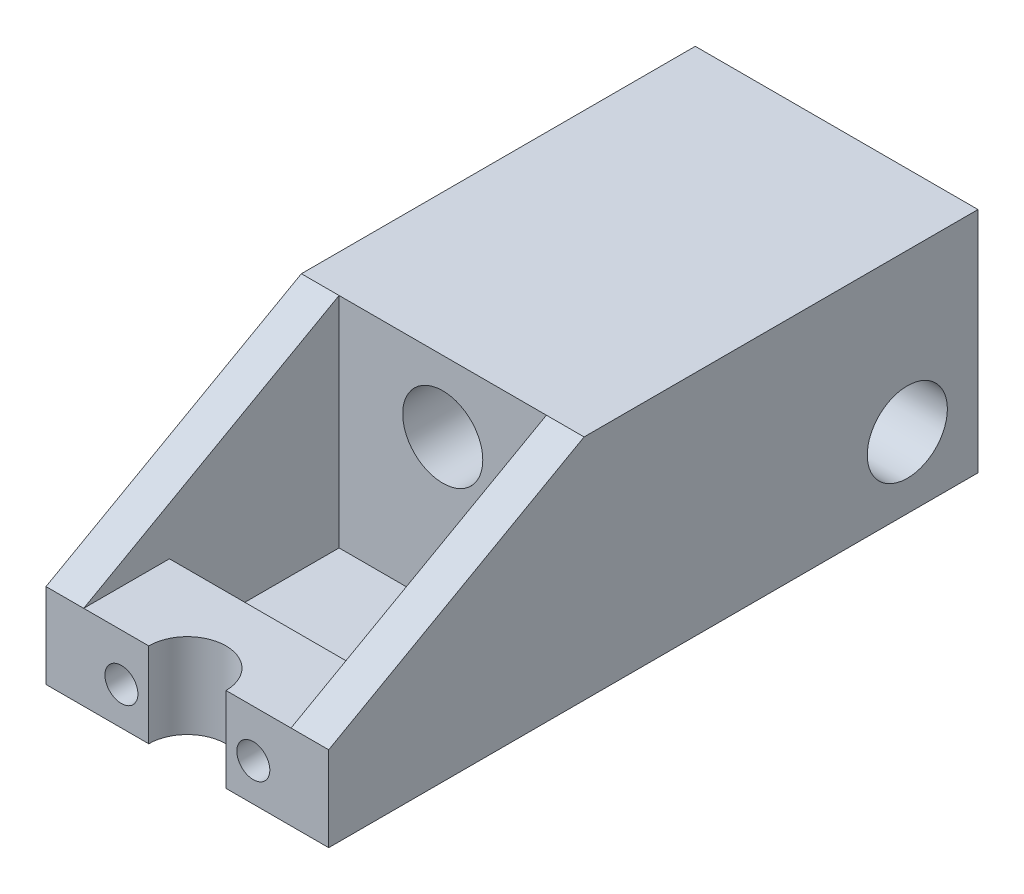
SolidWorks part; units mm, degrees
ref_plane "Piano frontale" through (0, 0, 0) normal (0, 0, 1) x (1, 0, 0)
ref_plane "Piano superiore" through (0, 0, 0) normal (0, 1, 0) x (1, 0, 0)
ref_plane "Piano destro" through (0, 0, 0) normal (1, 0, 0) x (0, 0, -1)
sketch "Schizzo7" plane through (0, 0, 0) normal (0, 0, 1) x (1, 0, 0)
  line L0 (0, -12.1) -> (0, 12.1) construction
  line L1 (15, -12.1) -> (-15, -12.1)
  line L2 (15, -12.1) -> (15, 12.1)
  line L3 (15, 12.1) -> (-15, 12.1)
  line L4 (-15, -12.1) -> (-15, 12.1)
  line L5 (15, -12.1) -> (-15, 12.1) construction
  line L6 (15, 12.1) -> (-15, -12.1) construction
  circle A0 centre (0, 4.6) radius 4.25
  point P0 (0, 0)
  point P10 (0, -4.6)
  dimension "D3" = 8.5
  dimension "D5" = 7.5
  dimension "D1" = 7.5
  dimension "D2" = 30
  dimension "D4" = 9.2
extrude "Estrusione-Estrusione3" add sketch "Schizzo7" along normal mid plane 15
sketch "Schizzo8" plane through (15, 0, 0) normal (1, 0, 0) x (0, 0, -1)
  line L0 (0, 12.1) -> (0, -12.1) construction
  line L1 (-7.5, 12.1) -> (7.5, 12.1) construction
  line L2 (-7.5, -12.1) -> (7.5, -12.1) construction
  circle A0 centre (0, -4.6) radius 4.25
  dimension "D2" = 8.5
  dimension "D1" = 7.5
extrude "Taglio-Estrusione1" cut sketch "Schizzo8" against normal up to next
sketch "Schizzo12" plane through (0, 0, 7.5) normal (0, 0, 1) x (1, 0, 0)
  line L0 (15, -12.1) -> (15, 12.1) construction
  line L1 (-15, -12.1) -> (15, -12.1)
  line L2 (-15, -12.1) -> (-15, -3.1)
  line L3 (-15, -3.1) -> (15, -3.1)
  line L4 (15, -12.1) -> (15, -3.1)
  dimension "D1" = 9
extrude "Estrusione-Estrusione5" add sketch "Schizzo12" along normal blind 53.9
sketch "Schizzo14" plane through (0, -3.1, 0) normal (0, 1, 0) x (1, 0, 0)
  line L0 (15, -61.4) -> (-15, -61.4) construction
  line L1 (4.1, -61.4) -> (-4.1, -61.4)
  arc A0 (4.1, -61.4) -> (-4.1, -61.4) centre (0, -61.4) ccw
  dimension "D1" = 4.1
extrude "Taglio-Estrusione3" cut sketch "Schizzo14" against normal up to next contours A0 L1
sketch "Schizzo15" plane through (0, -3.1, 0) normal (0, 1, 0) x (1, 0, 0)
  line L0 (15, -61.4) -> (4.1, -61.4) construction
  line L1 (0, -57.3) -> (0, -7.5) construction
  line L2 (15, -7.5) -> (-15, -7.5) construction
  line L3 (11, -52.3) -> (11, -34.3)
  line L4 (11, -34.3) -> (-11, -34.3)
  line L5 (-11, -52.3) -> (-11, -34.3)
  line L7 (15, -61.4) -> (15, -7.5) construction
  line L12 (11, -52.3) -> (-11, -52.3)
  arc A0 (4.1, -61.4) -> (-4.1, -61.4) centre (0, -61.4) ccw construction
  point P17 (0, -34.3)
  point P18 (0, -52.3)
  dimension "D1" = 9.1
  dimension "D2" = 18
  dimension "D4" = 4
sketch "Schizzo16" plane through (0, 0, 61.4) normal (0, 0, 1) x (1, 0, 0)
  line L0 (-4.1, -12.1) -> (4.1, -12.1) construction
  line L1 (-4.1, -12.1) -> (4.1, -12.1) construction
  line L2 (4.1, -3.1) -> (-4.1, -3.1) construction
  line L3 (4.1, -3.1) -> (-4.1, -3.1) construction
  line L4 (0, -12.1) -> (0, -3.1) construction
  line L5 (-4.1, -3.1) -> (-15, -3.1) construction
  circle A0 centre (-7, -8.1) radius 1.75
  circle A1 centre (7, -8.1) radius 1.75
  dimension "D2" = 3.5
  dimension "D1" = 5
  dimension "D3" = 7
extrude "Taglio-Estrusione4" cut sketch "Schizzo15" against normal blind 8
extrude "Taglio-Estrusione5" cut sketch "Schizzo16" against normal up to next
sketch "Schizzo17" plane through (0, 0, 52.3) normal (0, 0, -1) x (-1, 0, 0)
  line L0 (0, -3.1) -> (0, -11.1) construction
  line L1 (-3.75, -8.1) -> (-5.375, -5.2854)
  line L2 (-5.375, -5.2854) -> (-8.625, -5.2854)
  line L3 (-8.625, -5.2854) -> (-10.25, -8.1)
  line L4 (-10.25, -8.1) -> (-8.625, -10.9146)
  line L5 (-8.625, -10.9146) -> (-5.375, -10.9146)
  line L6 (-5.375, -10.9146) -> (-3.75, -8.1)
  line L7 (11, -3.1) -> (-11, -3.1) construction
  line L8 (11, -11.1) -> (-11, -11.1) construction
  line L9 (5.375, -10.9146) -> (3.75, -8.1)
  line L10 (8.625, -10.9146) -> (5.375, -10.9146)
  line L11 (10.25, -8.1) -> (8.625, -10.9146)
  line L12 (8.625, -5.2854) -> (10.25, -8.1)
  line L13 (5.375, -5.2854) -> (8.625, -5.2854)
  line L14 (3.75, -8.1) -> (5.375, -5.2854)
  circle A0 centre (-7, -8.1) radius 1.75 construction
  circle A1 centre (-7, -8.1) radius 1.75 construction
  circle A2 centre (-7, -8.1) radius 2.8146 construction
  circle A3 centre (7, -8.1) radius 2.8146 construction
  circle A4 centre (7, -8.1) radius 1.75 construction
  dimension "D1" = 6.5
extrude "Taglio-Estrusione6" cut sketch "Schizzo17" against normal blind 3.1 contours L1 L2 L3 L4 L5 L6 | L14 L13 L12 L11 L10 L9
sketch "Schizzo20" plane through (0, 0, 7.5) normal (0, 0, 1) x (1, 0, 0)
  line L4 (-15, -3.1) -> (15, -3.1)
  line L5 (15, -3.1) -> (15, 12.1)
  line L6 (15, 12.1) -> (-15, 12.1)
  line L7 (-15, 12.1) -> (-15, -3.1)
  line L8 (-15, -3.1) -> (15, -3.1)
  line L9 (15, -3.1) -> (15, 12.1)
  line L10 (15, 12.1) -> (-15, 12.1)
  line L11 (-15, 12.1) -> (-15, -3.1)
  line M5 (-15, -3.1) -> (15, -3.1)
  line M6 (15, -3.1) -> (15, 12.1)
  line M7 (15, 12.1) -> (-15, 12.1)
  line M8 (-15, 12.1) -> (-15, -3.1)
  circle M9 centre (0, 4.6) radius 4.25
  dimension "D1" = 0
extrude "Estrusione-Estrusione6" add sketch "Schizzo20" along normal up to vertex contours M8 M5 M6 M7 M9
sketch "Schizzo21" plane through (-15, 0, 0) normal (-1, 0, 0) x (0, 0, 1)
  line L0 (34.3, 12.1) -> (61.4, -3.1)
  line L1 (61.4, -3.1) -> (34.3, -3.1)
  line L2 (34.3, -3.1) -> (34.3, 12.1)
extrude "Estrusione-Estrusione7" add sketch "Schizzo21" against normal up to vertex (4 mm away) up to point (-11, -3.1, 52.3)
sketch "Schizzo22" plane through (15, 0, 0) normal (1, 0, 0) x (0, 0, -1)
  line L0 (-34.3, 12.1) -> (-61.4, -3.1)
  line L1 (-61.4, -3.1) -> (-34.3, -3.1)
  line L2 (-34.3, -3.1) -> (-34.3, 12.1)
extrude "Estrusione-Estrusione8" add sketch "Schizzo22" against normal up to vertex
